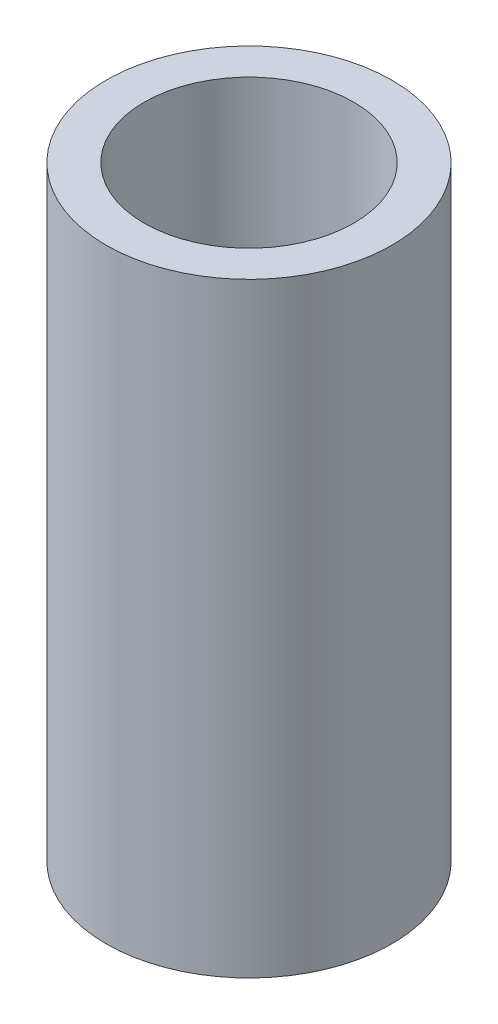
SolidWorks part; units mm, degrees
ref_plane "Front Plane" through (0, 0, 0) normal (0, 0, 1) x (1, 0, 0)
ref_plane "Top Plane" through (0, 0, 0) normal (0, 1, 0) x (1, 0, 0)
ref_plane "Right Plane" through (0, 0, 0) normal (1, 0, 0) x (0, 0, -1)
sketch "Sketch1" plane through (-40.8286, 6.5474, -7.3141) normal (0, 1, 0) x (1, 0, 0)
  circle A0 centre (9.677, 16.7399) radius 1.5
  dimension "D1" = 3
extrude "Boss-Extrude1" add sketch "Sketch1" along normal blind 6.35
sketch "Sketch2" plane through (0, 6.5474, 0) normal (0, -1, 0) x (-1, 0, 0)
  circle A0 centre (31.1516, 24.054) radius 1.1
  dimension "D1" = 2.2
extrude "Cut-Extrude1" cut sketch "Sketch2" against normal blind 6.35
